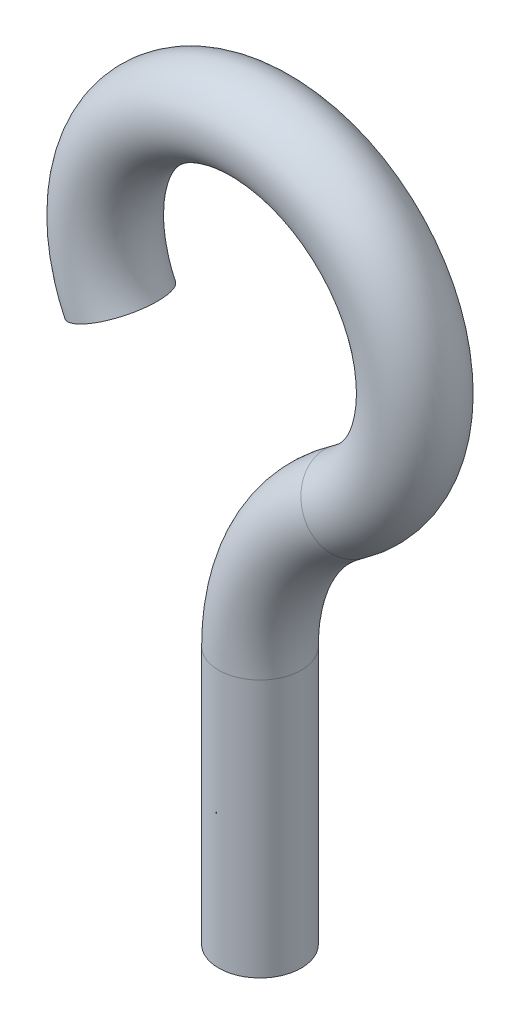
SolidWorks part; units mm, degrees
ref_plane "Ön Düzlem" through (0, 0, 0) normal (0, 0, 1) x (1, 0, 0)
ref_plane "Üst Düzlem" through (0, 0, 0) normal (0, 1, 0) x (1, 0, 0)
ref_plane "Sağ Düzlem" through (0, 0, 0) normal (1, 0, 0) x (0, 0, -1)
sketch "Çizim3" plane through (0, 0, 0) normal (0, 0, 1) x (1, 0, 0)
  line L0 (0, 0) -> (0, 25)
  arc A0 (0, 25) -> (8.5714, 41.413) centre (20, 25) cw
  arc A4 (8.5714, 41.413) -> (-13.5417, 47.2712) centre (0, 53.7228) ccw
  point P7 (0, 0)
  point P8 (0, 0)
  point P9 (0, 0)
  dimension "D1" = 25
  dimension "D2" = 20
  dimension "D3" = 15
ref_plane "Düzlem1" through (0, 0, 0) normal (0, 1, 0) x (1, 0, 0)
sketch "Çizim4" plane through (0, 0, 0) normal (0, 1, 0) x (1, 0, 0)
  circle A0 centre (0, 0) radius 4
  circle A1 centre (0, 0) radius 3
  dimension "D1" = 8
  dimension "D2" = 6
sweep "Süpür1" add profiles "Çizim4" path "Çizim3"
